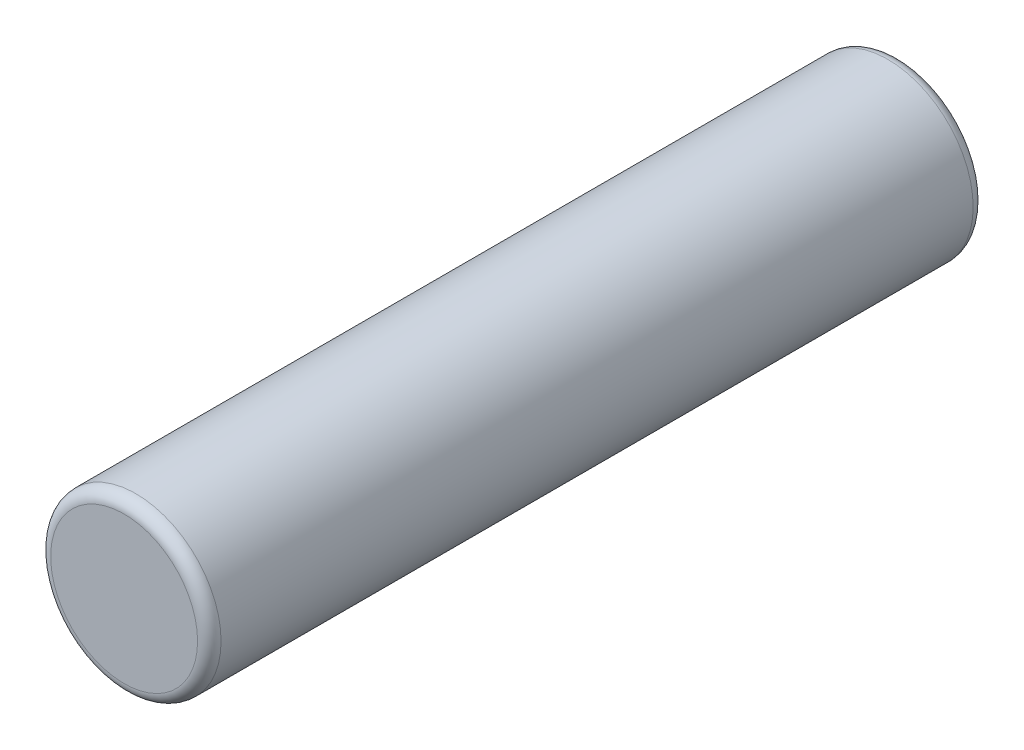
SolidWorks part; units mm, degrees
ref_plane "Front Plane" through (0, 0, 0) normal (0, 0, 1) x (1, 0, 0)
ref_plane "Top Plane" through (0, 0, 0) normal (0, 1, 0) x (1, 0, 0)
ref_plane "Right Plane" through (0, 0, 0) normal (1, 0, 0) x (0, 0, -1)
sketch "Sketch2" plane through (0, 0, 0) normal (0, 0, 1) x (1, 0, 0)
  line L0 (-7.25, 0) -> (7.25, 0) construction
  line L1 (0, 7.25) -> (0, -7.25) construction
  circle A0 centre (0, 0) radius 7.25
  dimension "D1" = 14.5
extrude "Boss-Extrude1" add sketch "Sketch2" along normal mid plane 66
fillet "Fillet1" radius 1 2 edges at (7.25, 0, -33) (7.25, 0, 33)
